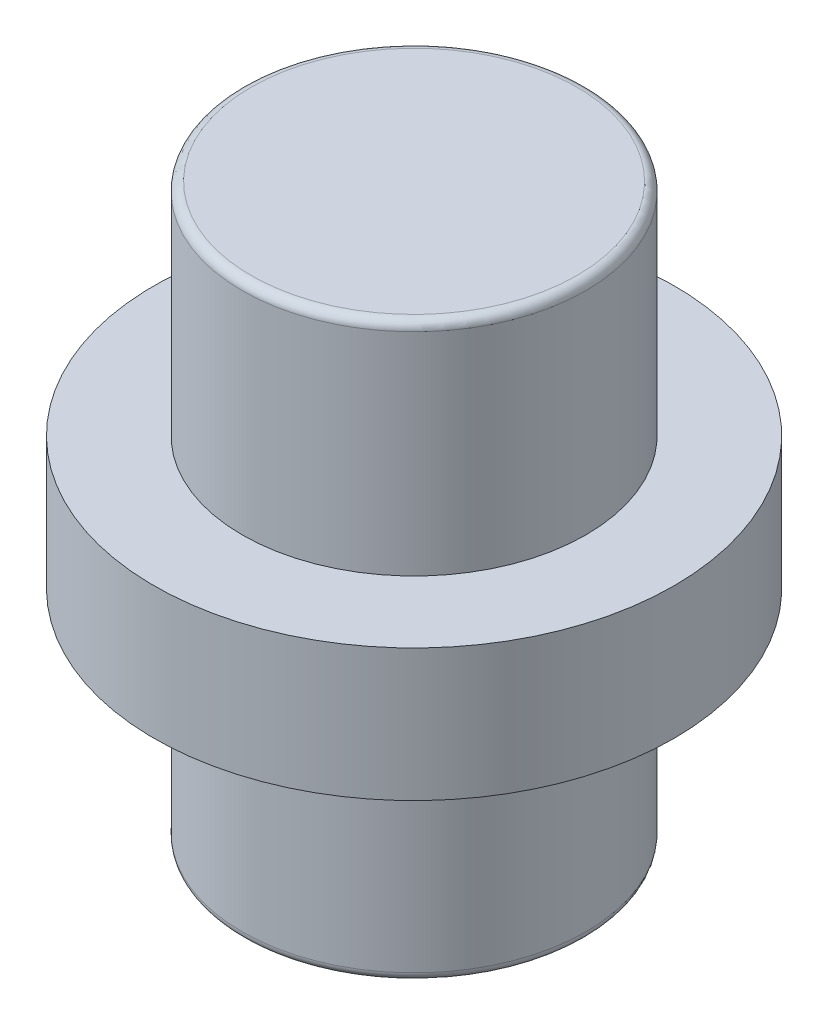
SolidWorks part; units mm, degrees
ref_plane "Front Plane" through (0, 0, 0) normal (0, 0, 1) x (1, 0, 0)
ref_plane "Top Plane" through (0, 0, 0) normal (0, 1, 0) x (1, 0, 0)
ref_plane "Right Plane" through (0, 0, 0) normal (1, 0, 0) x (0, 0, -1)
sketch "Sketch1" plane through (0, 0, 0) normal (0, 0, 1) x (1, 0, 0)
  line L0 (0, 0) -> (3.9, 0)
  line L1 (3.9, 0) -> (3.9, 5)
  line L2 (3.9, 5) -> (5.9, 5)
  line L3 (5.9, 5) -> (5.9, 8)
  line L4 (5.9, 8) -> (3.9, 8)
  line L5 (3.9, 8) -> (3.9, 13)
  line L6 (3.9, 13) -> (0, 13)
  line L7 (0, 0) -> (0, 13)
  dimension "D1" = 3.9
  dimension "D2" = 5
  dimension "D3" = 2
  dimension "D4" = 3
  dimension "D5" = 2
  dimension "D6" = 5
  dimension "D7" = 3.9
revolve "Revolve1" add sketch "Sketch1" angle 360 about L7
fillet "Fillet1" radius 0.2 2 edges at (3.9, 0, 0) (3.9, 13, 0)
